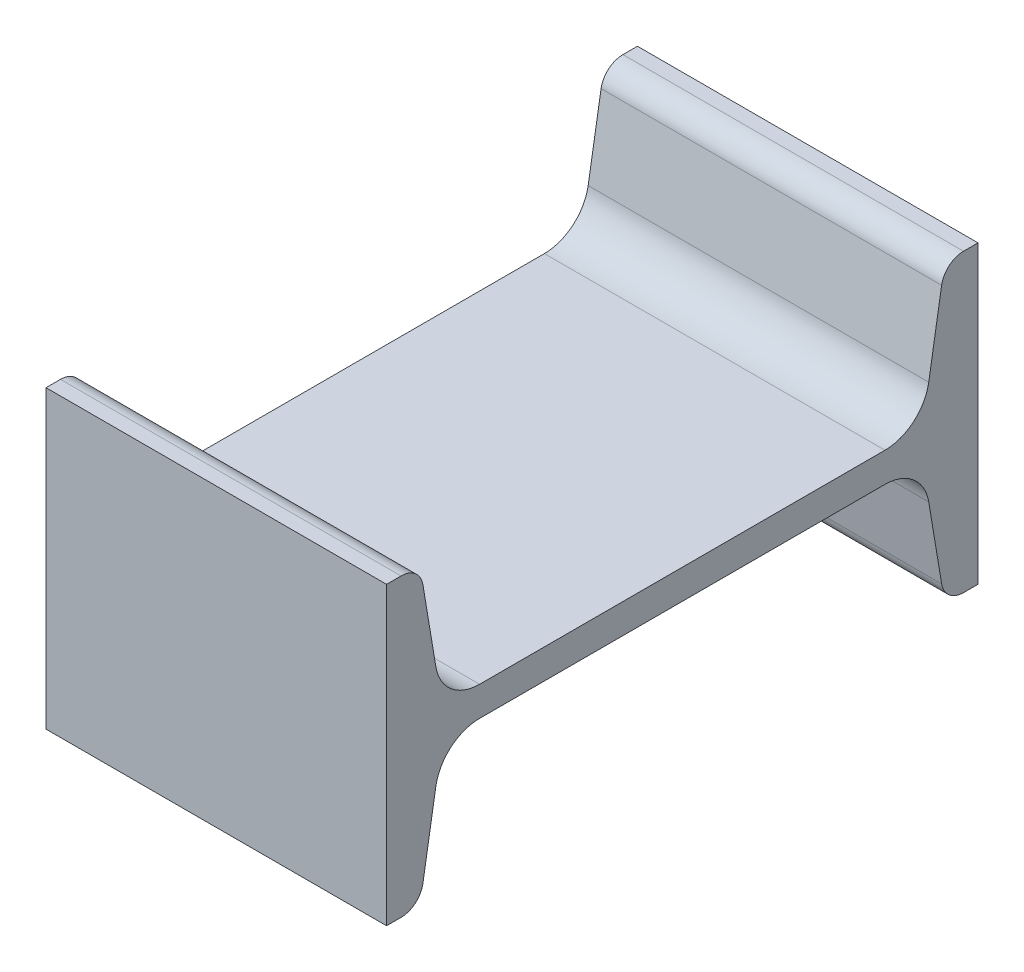
SolidWorks part; units mm, degrees
material "Yumuşak Demir"
ref_plane "Ön Düzlem" through (0, 0, 0) normal (0, 0, 1) x (1, 0, 0)
ref_plane "Üst Düzlem" through (0, 0, 0) normal (0, 1, 0) x (1, 0, 0)
ref_plane "Sağ Düzlem" through (0, 0, 0) normal (1, 0, 0) x (0, 0, -1)
sketch "Çizim1" plane through (0, 0, 0) normal (0, 0, 1) x (1, 0, 0)
  line L0 (0, 0) -> (46.0686, 0)
other "Sb kiriş 80 X 6(1)"
ref_plane "Düzlem1" through (0, 0, 0) normal (1, 0, 0) x (0, 1, 0)
sketch "Sketch14" plane through (0, 0, 0) normal (1, 0, 0) x (0, 1, 0)
  line L0 (-20, -40) -> (-20, -38.0415)
  line L1 (-17.4932, -35.0823) -> (-7.0135, -33.3355)
  line L2 (-2, -27.4172) -> (-2, 27.4172)
  line L3 (-7.0135, 33.3355) -> (-17.4932, 35.0823)
  line L4 (-20, 38.0415) -> (-20, 40)
  line L5 (-20, 40) -> (20, 40)
  line L6 (20, 40) -> (20, 38.0415)
  line L7 (17.4932, 35.0823) -> (7.0135, 33.3355)
  line L8 (2, 27.4172) -> (2, -27.4172)
  line L9 (7.0135, -33.3355) -> (17.4932, -35.0823)
  line L10 (20, -38.0415) -> (20, -40)
  line L11 (20, -40) -> (-20, -40)
  line L15 (-2, 0) -> (2, 0) construction
  arc A0 (-7.0135, -33.3355) -> (-2, -27.4172) centre (-8, -27.4172) ccw
  arc A1 (-2, 27.4172) -> (-7.0135, 33.3355) centre (-8, 27.4172) ccw
  arc A2 (7.0135, 33.3355) -> (2, 27.4172) centre (8, 27.4172) ccw
  arc A3 (2, -27.4172) -> (7.0135, -33.3355) centre (8, -27.4172) ccw
  arc A4 (-17.4932, 35.0823) -> (-20, 38.0415) centre (-17, 38.0415) cw
  arc A5 (17.4932, 35.0823) -> (20, 38.0415) centre (17, 38.0415) ccw
  arc A6 (-20, -38.0415) -> (-17.4932, -35.0823) centre (-17, -38.0415) cw
  arc A7 (20, -38.0415) -> (17.4932, -35.0823) centre (17, -38.0415) ccw
  point P1 (0, 40)
  point P8 (0, -40)
  point P21 (0, 0)
  point P34 (0, 0)
  dimension "RI" = 6
  dimension "D3" = 3
  dimension "BF" = 40
  dimension "D2" = 9.463
  dimension "DEPTH" = 80
  dimension "TW" = 4
  dimension "D1" = 54.8344
